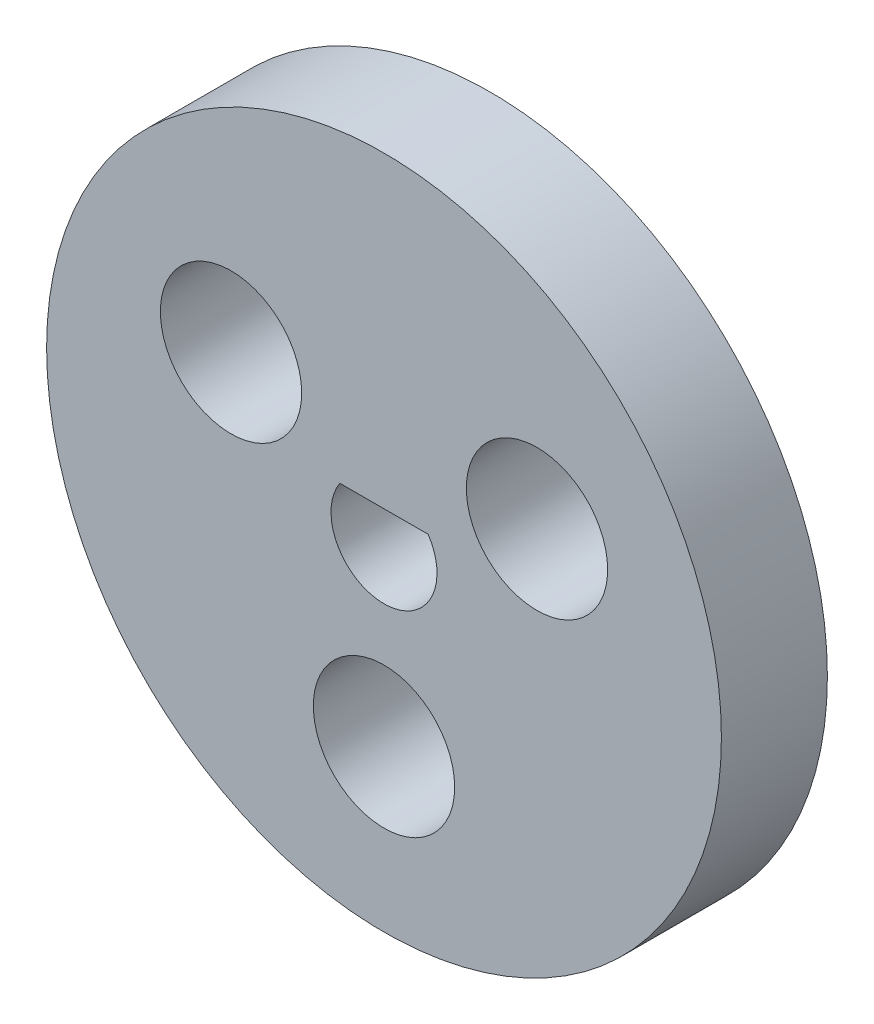
SolidWorks part; units mm, degrees
ref_plane "Front Plane" through (0, 0, 0) normal (0, 0, 1) x (1, 0, 0)
ref_plane "Top Plane" through (0, 0, 0) normal (0, 1, 0) x (1, 0, 0)
ref_plane "Right Plane" through (0, 0, 0) normal (1, 0, 0) x (0, 0, -1)
sketch "Sketch1" plane through (0, 0, 0) normal (0, 0, 1) x (1, 0, 0)
  line L0 (1.25, 0.8292) -> (-1.25, 0.8292)
  line L1 (-4.3301, 2.5) -> (0, 0) construction
  line L2 (0, 0) -> (4.3301, 2.5) construction
  line L3 (0, -5) -> (0, 0) construction
  circle A2 centre (0, 0) radius 9.55
  circle A6 centre (0, -5) radius 2
  circle A7 centre (4.3301, 2.5) radius 2
  circle A8 centre (0, 0) radius 1.5
  circle A9 centre (-4.3301, 2.5) radius 2
  point P6 (0, 0)
  point P7 (0, 0)
  dimension "D2" = 19.1
  dimension "D3" = 4
  dimension "D4" = 4
  dimension "D5" = 4
  dimension "D11" = 3
  dimension "D1" = 2.5
  dimension "D6" = 5
  dimension "D7" = 5
  dimension "D8" = 5
  dimension "D9" = 120
  dimension "D10" = 120
extrude "Boss-Extrude1" add sketch "Sketch1" along normal blind 3 contours A2 A9 A8 A7 A6 | L0 A8
